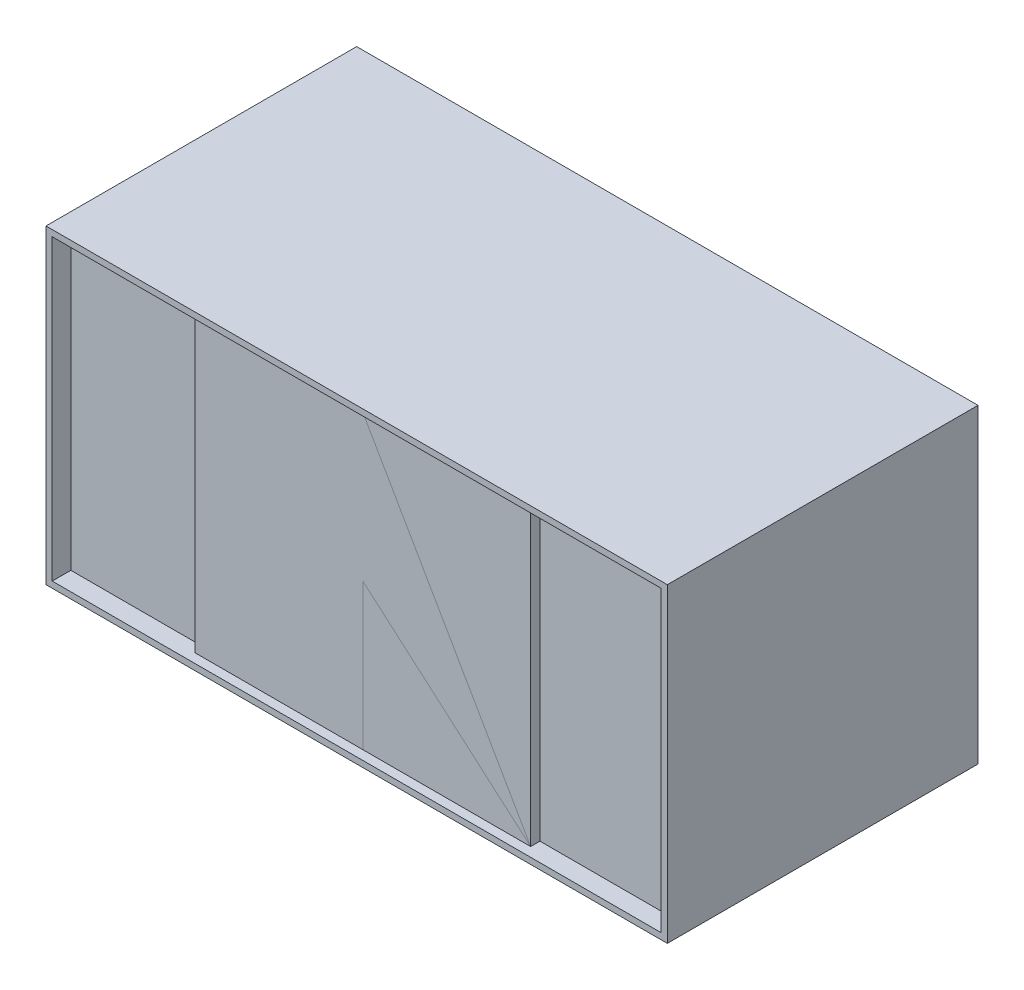
SolidWorks part; units mm, degrees
other "Cabine sem Portas"
ref_plane "Plano frontal" through (0, 0, 0) normal (0, 0, 1) x (1, 0, 0)
ref_plane "Plano superior" through (0, 0, 0) normal (0, 1, 0) x (1, 0, 0)
ref_plane "Plano direito" through (0, 0, 0) normal (1, 0, 0) x (0, 0, -1)
ref_plane "Parede Frontal" through (0, 0, 210) normal (0, 0, 1) x (1, 0, 0)
ref_plane "Interna Esquerda" through (-250, 0, 0) normal (1, 0, 0) x (0, 0, -1)
ref_plane "Interna Direita" through (250, 0, 0) normal (1, 0, 0) x (0, 0, -1)
ref_plane "Portas" through (0, 0, 225) normal (0, 0, 1) x (1, 0, 0)
sketch "Esboço1" plane through (0, 0, 0) normal (0, 0, 1) x (1, 0, 0)
  line L1 (500, -250) -> (-500, -250)
  line L2 (500, -250) -> (500, 250)
  line L3 (500, 250) -> (-500, 250)
  line L4 (-500, -250) -> (-500, 250)
  line L5 (500, -250) -> (-500, 250) construction
  line L6 (500, 250) -> (-500, -250) construction
  point P0 (0, 0)
  dimension "D1" = 500
  dimension "D2" = 1000
extrude "Ressalto-extrusão1" add sketch "Esboço1" along normal mid plane 500
shell "Casca1" thickness 10
sketch "Esboço3" plane through (0, 0, -250) normal (0, 0, -1) x (-1, 0, 0)
  line L0 (0, 879.4708) -> (0, -379.4708) construction
  line L2 (200, -200) -> (-200, -200)
  line L3 (200, -200) -> (200, 200)
  line L6 (-200, -200) -> (-200, 200)
  line L8 (200, -200) -> (-200, 200) construction
  line L9 (200, 200) -> (-200, -200) construction
  line L11 (500, -250) -> (-500, -250) construction
  line L12 (-200, 200) -> (200, 200)
  point P3 (24.2849, 144.2462)
  point P6 (0, 250)
  point P7 (0, 250)
  point P9 (0, 0)
  dimension "D1" = 400
  dimension "D2" = 400
  dimension "D4" = 50
other "Alinhar grupo1"
extrude "Corte-extrusão5" cut sketch "Esboço3" against normal mid plane 500 contours L12 L3 L2 L6
other "Salvar corpos1"
sketch "Esboço19" plane through (0, 0, 0) normal (0, 0, 1) x (1, 0, 0)
  line L4 (-220, -1223.6407) -> (-220, 48776.3593)
sketch "Esboço21" plane through (0, 0, 210) normal (0, 0, 1) x (1, 0, 0)
  line L0 (-220, -201223.6407) -> (-220, 248776.3593) construction
  line L1 (-490, 240) -> (-220, 240)
  line L2 (-490, 240) -> (-490, -240)
  line L3 (-490, -240) -> (-220, -240)
  line L4 (-220, 240) -> (-220, -240)
  line L5 (-490, -240) -> (490, -240) construction
extrude "Ressalto-extrusão3" add sketch "Esboço21" along normal blind 10
pattern_linear "Padrão linear1" count 2 spacing 710 along (1, 0, 0) of "Ressalto-extrusão3"
sketch "Esboço24" plane through (0, 0, 220) normal (0, 0, 1) x (1, 0, 0)
  circle A0 centre (-260, -220) radius 4
extrude "Corte-extrusão7" cut sketch "Esboço24" against normal mid plane 50
sketch "Esboço33" plane through (0, 0, 225) normal (0, 0, 1) x (1, 0, 0)
  line L0 (0, -750) -> (0, 49250)
sketch "Esboço34" plane through (-250, 0, 0) normal (1, 0, 0) x (0, 0, -1)
  line L0 (-250, -250) -> (250, -250) construction
  line L1 (250, 250) -> (-210, 250)
  line L2 (250, 250) -> (250, -250)
  line L3 (250, -250) -> (-210, -250)
  line L4 (-210, 250) -> (-210, -250)
extrude "Ressalto-extrusão6" add sketch "Esboço34" against normal blind 10
sketch "Esboço35" plane through (250, 0, 0) normal (1, 0, 0) x (0, 0, -1)
  line L1 (240, 240) -> (-210, 240)
  line L2 (240, 240) -> (240, -240)
  line L3 (240, -240) -> (-210, -240)
  line L4 (-210, 240) -> (-210, -240)
extrude "Ressalto-extrusão7" add sketch "Esboço35" along normal blind 10
sketch "Esboço36" plane through (0, 0, 225) normal (0, 0, 1) x (1, 0, 0)
  line L0 (0, -200750) -> (0, 249250) construction
  line L1 (0, -235) -> (-270, -235)
  line L2 (0, -235) -> (0, 235)
  line L3 (0, 235) -> (-270, 235)
  line L4 (-270, -235) -> (-270, 235)
  line L5 (490, 240) -> (-490, 240) construction
  dimension "D1" = 5
extrude "Ressalto-extrusão8" add sketch "Esboço36" along normal blind 15
mirror "Espelhar5" about plane through (0, -235, 240) normal (-1, 0, 0) of bodies 128
mirror "Espelhar4" about plane through (0, -235, 240) normal (-1, 0, 0) of "Ressalto-extrusão8"
other "Salvar corpos2" [suppressed]
